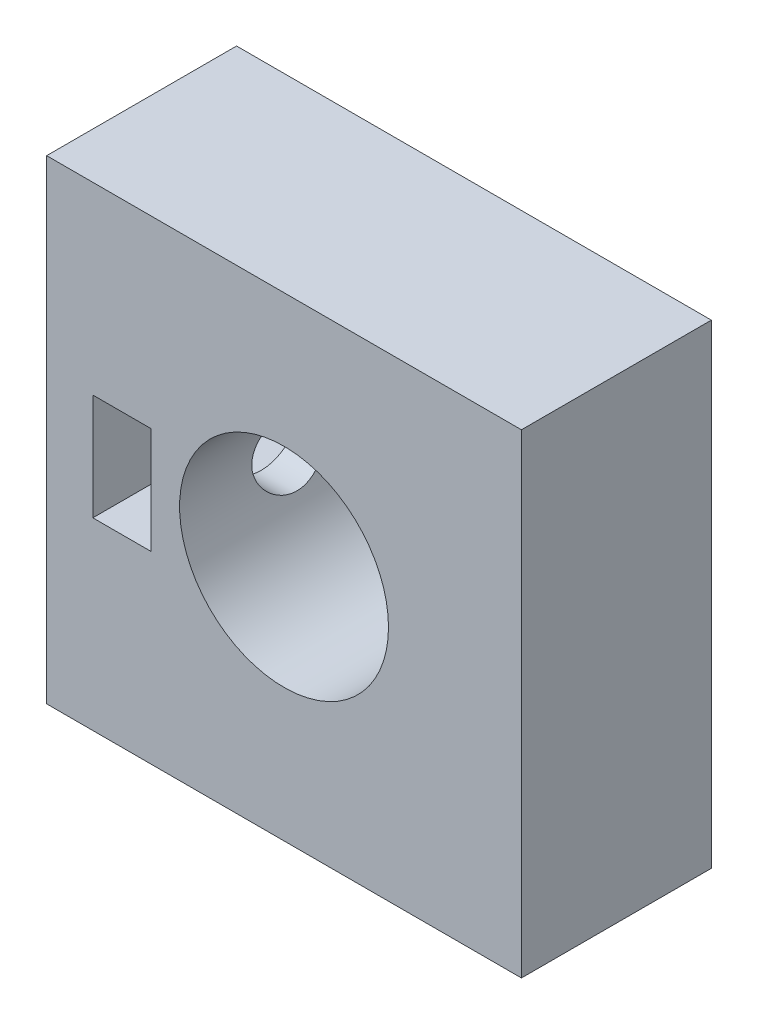
SolidWorks part; units mm, degrees
ref_plane "Alzado" through (0, 0, 0) normal (0, 0, 1) x (1, 0, 0)
ref_plane "Planta" through (0, 0, 0) normal (0, 1, 0) x (1, 0, 0)
ref_plane "Vista lateral" through (0, 0, 0) normal (1, 0, 0) x (0, 0, -1)
sketch "Croquis1" plane through (0, 0, 0) normal (0, 0, 1) x (1, 0, 0)
  line L0 (12.5, 25) -> (12.5, 0) construction
  line L1 (0, 0) -> (25, 0)
  line L2 (0, 0) -> (0, 25)
  line L3 (0, 25) -> (25, 25)
  line L4 (25, 0) -> (25, 25)
  line L5 (25, 12.5) -> (0, 12.5) construction
  circle A0 centre (12.5, 12.5) radius 5.5
  dimension "D2" = 11
  dimension "D1" = 25
extrude "Saliente-Extruir1" add sketch "Croquis1" along normal blind 10
sketch "Croquis2" plane through (0, 0, 0) normal (-1, 0, 0) x (0, 0, 1)
  line L0 (0, 12.5) -> (10, 12.5) construction
  line L1 (0, 25) -> (0, 0) construction
  line L2 (10, 25) -> (10, 0) construction
  circle A0 centre (4.2, 12.5) radius 2
  dimension "D1" = 4
  dimension "D2" = 4.2
extrude "Cortar-Extruir1" cut sketch "Croquis2" against normal up to next
sketch "Croquis3" plane through (0, 0, 0) normal (0, 0, -1) x (-1, 0, 0)
  line L0 (-12.5, 0) -> (-12.5, 12.5) construction
  line L1 (-5.5, 15.3) -> (-2.432, 15.3)
  line L2 (-5.5, 15.3) -> (-5.5, 9.7)
  line L3 (-5.5, 9.7) -> (-2.432, 9.7)
  line L4 (-2.432, 15.3) -> (-2.432, 9.7)
  line L5 (0, 0) -> (-25, 0) construction
  line L6 (-25, 12.5) -> (-12.5, 12.5) construction
  line L7 (-25, 0) -> (-25, 25) construction
  dimension "D1" = 5.6
  dimension "D2" = 3.068
  dimension "D3" = 7
  dimension "D4" = 2.8
extrude "Cortar-Extruir2" cut sketch "Croquis3" against normal through all
